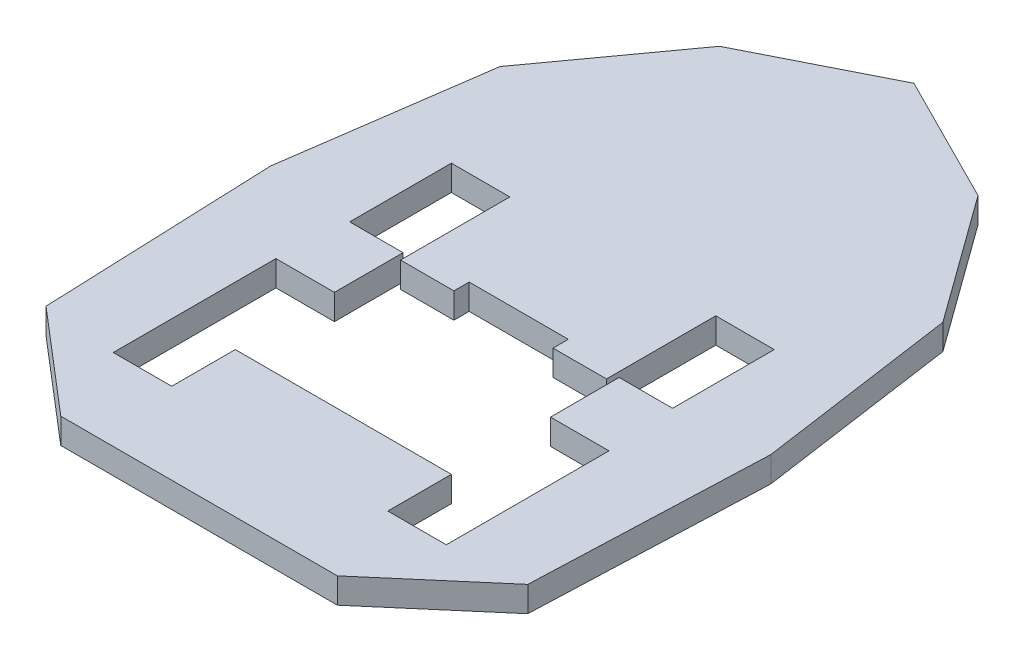
SolidWorks part; units mm, degrees
ref_plane "Front Plane" through (0, 0, 0) normal (0, 0, 1) x (1, 0, 0)
ref_plane "Top Plane" through (0, 0, 0) normal (0, 1, 0) x (1, 0, 0)
ref_plane "Right Plane" through (0, 0, 0) normal (1, 0, 0) x (0, 0, -1)
sketch "Sketch1" plane through (0, 0, 0) normal (0, 1, 0) x (1, 0, 0)
  line L0 (212.5, -536.8767) -> (327.5, -536.8767)
  line L1 (327.5, -536.8767) -> (327.5, -216.8767)
  line L5 (327.5, -216.8767) -> (212.5, -216.8767)
  line L15 (212.5, -216.8767) -> (212.5, -536.8767)
  line L20 (-490.4158, -64.1941) -> (-472.4779, -524.1388)
  line L21 (-472.4779, -524.1388) -> (-270.661, -696.8767)
  line L22 (-270.661, -696.8767) -> (273.2432, -696.8767)
  line L23 (475.0601, -524.1388) -> (273.2432, -696.8767)
  line L24 (492.9981, -64.1941) -> (475.0601, -524.1388)
  line L25 (436.8035, 330.5116) -> (492.9981, -64.1941)
  line L26 (255.5269, 580.8273) -> (436.8035, 330.5116)
  line L27 (1.2911, 709.0589) -> (255.5269, 580.8273)
  line L28 (1.2911, 709.0589) -> (-252.9446, 580.8273)
  line L29 (-252.9446, 580.8273) -> (-434.2212, 330.5116)
  line L30 (-434.2212, 330.5116) -> (-490.4158, -64.1941)
  line L31 (0, 0) -> (0, -397.0024) construction
  line L32 (212.5, -411.8767) -> (97.5, -411.8767)
  line L33 (212.5, -411.8767) -> (212.5, -96.8767)
  line L34 (202.5, -96.8767) -> (97.5, -96.8767)
  line L35 (97.5, -411.8767) -> (97.5, -96.8767)
  line L36 (202.5, 118.1233) -> (317.5, 118.1233)
  line L37 (202.5, 118.1233) -> (202.5, -81.8767)
  line L38 (212.5, -81.8767) -> (317.5, -81.8767)
  line L39 (317.5, 118.1233) -> (317.5, -81.8767)
  line L40 (97.5, -96.8767) -> (97.5, -66.8767)
  line L41 (97.5, -66.8767) -> (-97.5, -66.8767)
  line L42 (97.5, -411.8767) -> (-97.5, -411.8767)
  line L43 (-97.5, -96.8767) -> (-97.5, -66.8767)
  line L44 (-317.5, 118.1233) -> (-317.5, -81.8767)
  line L45 (-212.5, -81.8767) -> (-317.5, -81.8767)
  line L46 (-202.5, 118.1233) -> (-202.5, -81.8767)
  line L47 (-202.5, 118.1233) -> (-317.5, 118.1233)
  line L48 (-97.5, -411.8767) -> (-97.5, -96.8767)
  line L49 (-202.5, -96.8767) -> (-97.5, -96.8767)
  line L50 (-212.5, -411.8767) -> (-212.5, -96.8767)
  line L51 (-212.5, -411.8767) -> (-97.5, -411.8767)
  line L52 (-212.5, -216.8767) -> (-212.5, -536.8767)
  line L53 (-327.5, -216.8767) -> (-212.5, -216.8767)
  line L54 (-327.5, -536.8767) -> (-327.5, -216.8767)
  line L55 (-212.5, -536.8767) -> (-327.5, -536.8767)
  line L56 (212.5, -96.8767) -> (212.5, -81.8767)
  line L57 (202.5, -81.8767) -> (202.5, -96.8767)
  line L58 (-202.5, -81.8767) -> (-202.5, -96.8767)
  line L59 (-212.5, -96.8767) -> (-212.5, -81.8767)
  point P14 (150, -96.8767)
  point P19 (0, -411.8767)
  point P20 (0, -66.8767)
  dimension "D1" = 115
  dimension "D2" = 320
  dimension "D3" = 125
  dimension "D4" = 115
  dimension "D5" = 120
  dimension "D6" = 115
  dimension "D7" = 200
  dimension "D8" = 10
  dimension "D9" = 15
  dimension "D10" = 150
  dimension "D11" = 30
  dimension "D12" = 160
extrude "Boss-Extrude1" add sketch "Sketch1" against normal blind 50
